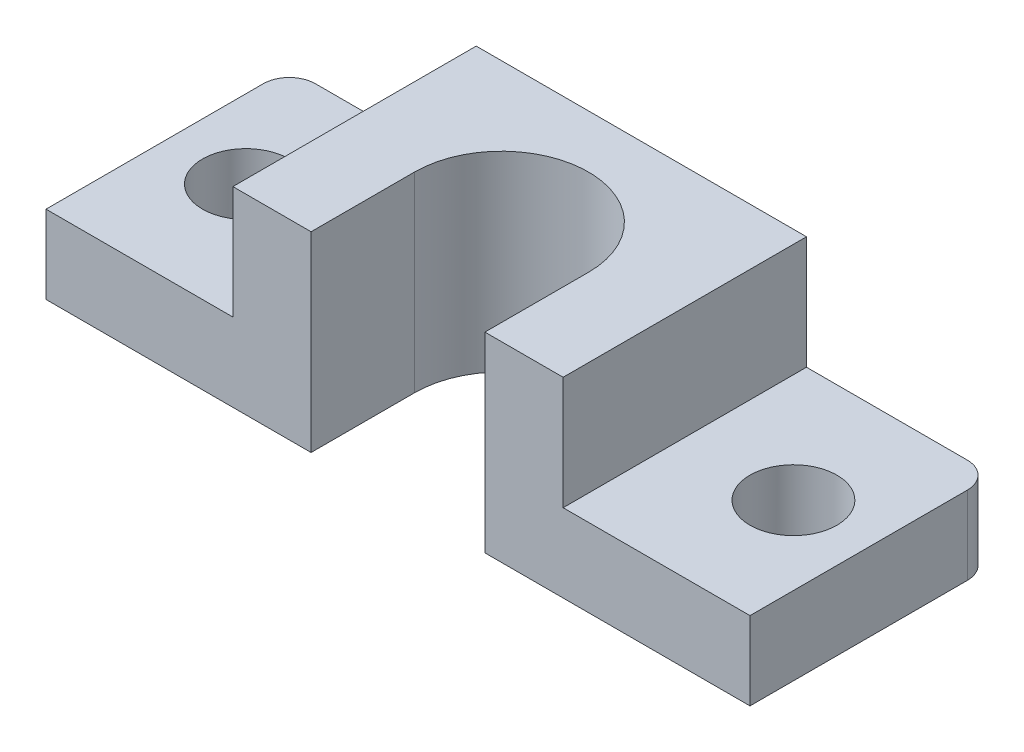
SolidWorks part; units mm, degrees
ref_plane "정면" through (0, 0, 0) normal (0, 0, 1) x (1, 0, 0)
ref_plane "윗면" through (0, 0, 0) normal (0, 1, 0) x (1, 0, 0)
ref_plane "우측면" through (0, 0, 0) normal (1, 0, 0) x (0, 0, -1)
sketch "스케치1" plane through (0, 0, 0) normal (0, 1, 0) x (1, 0, 0)
  line L1 (0, 0) -> (81, 0)
  line L2 (0, 0) -> (0, 28)
  line L3 (0, 28) -> (81, 28)
  line L4 (81, 0) -> (81, 28)
  dimension "D1" = 81
  dimension "D2" = 28
extrude "보스-돌출1" add sketch "스케치1" along normal blind 9
sketch "스케치2" plane through (0, 9, 0) normal (0, 1, 0) x (1, 0, 0)
  line L0 (81, 28) -> (0, 28) construction
  line L1 (21.5, 28) -> (59.5, 28)
  line L2 (21.5, 28) -> (21.5, 0)
  line L3 (21.5, 0) -> (59.5, 0)
  line L4 (59.5, 28) -> (59.5, 0)
  line L5 (0, 0) -> (81, 0) construction
  line L6 (0, 28) -> (0, 0) construction
  dimension "D1" = 0
  dimension "D2" = 0
  dimension "D3" = 38
  dimension "D4" = 21.5
extrude "보스-돌출2" add sketch "스케치2" along normal blind 13
sketch "스케치3" plane through (0, 22, 0) normal (0, 1, 0) x (1, 0, 0)
  line L0 (30.5, 0) -> (30.5, 11.9149)
  line L1 (21.5, 0) -> (59.5, 0) construction
  line L2 (50.5, 11.9149) -> (50.5, 0)
  line L3 (50.5, 0) -> (30.5, 0)
  line L4 (21.5, 28) -> (21.5, 0) construction
  arc A0 (50.5, 11.9149) -> (30.5, 11.9149) centre (40.5, 11.9149) ccw
  dimension "D1" = 10
  dimension "D2" = 9
extrude "컷-돌출1" cut sketch "스케치3" against normal blind 33
sketch "스케치4" plane through (0, 9, 0) normal (0, 1, 0) x (1, 0, 0)
  line L0 (0, 28) -> (0, 0) construction
  line L2 (0, 0) -> (21.5, 0) construction
  circle A0 centre (9, 14) radius 5
  dimension "D1" = 10
  dimension "D2" = 9
  dimension "D3" = 14
extrude "컷-돌출2" cut sketch "스케치4" against normal blind 33
sketch "스케치5" plane through (0, 9, 0) normal (0, 1, 0) x (1, 0, 0)
  line L0 (59.5, 0) -> (81, 0) construction
  line L1 (81, 0) -> (81, 28) construction
  circle A0 centre (72, 14) radius 5
  dimension "D3" = 10
  dimension "D1" = 14
  dimension "D2" = 9
extrude "컷-돌출3" cut sketch "스케치5" against normal blind 33
fillet "필렛1" radius 3 2 edges at (81, 4.5, -28) (0, 4.5, -28)
